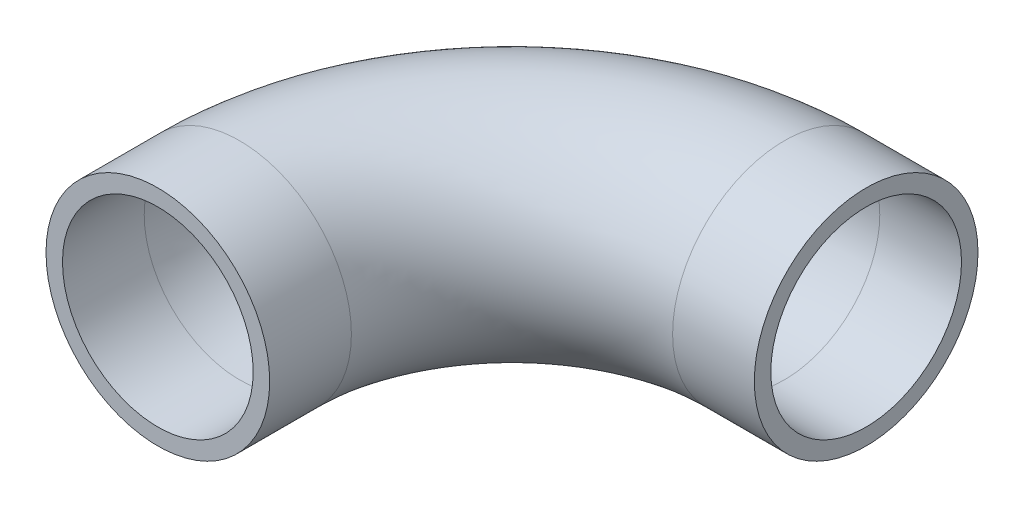
SolidWorks part; units mm, degrees
ref_plane "Front Plane" through (0, 0, 0) normal (0, 0, 1) x (1, 0, 0)
ref_plane "Top Plane" through (0, 0, 0) normal (0, 1, 0) x (1, 0, 0)
ref_plane "Right Plane" through (0, 0, 0) normal (1, 0, 0) x (0, 0, -1)
sketch "Sketch1" plane through (0, 0, 0) normal (0, 0, 1) x (1, 0, 0)
  circle A0 centre (0, 0) radius 7
  circle A1 centre (0, 0) radius 8.21
sketch "Sketch2" plane through (0, 0, 0) normal (0, 1, 0) x (1, 0, 0)
  line L0 (20, 26) -> (26, 26)
  line L1 (0, 6) -> (0, 0)
  arc A0 (20, 26) -> (0, 6) centre (20, 6) ccw
sweep "Sweep1" add profiles "Sketch1" path "Sketch2"
